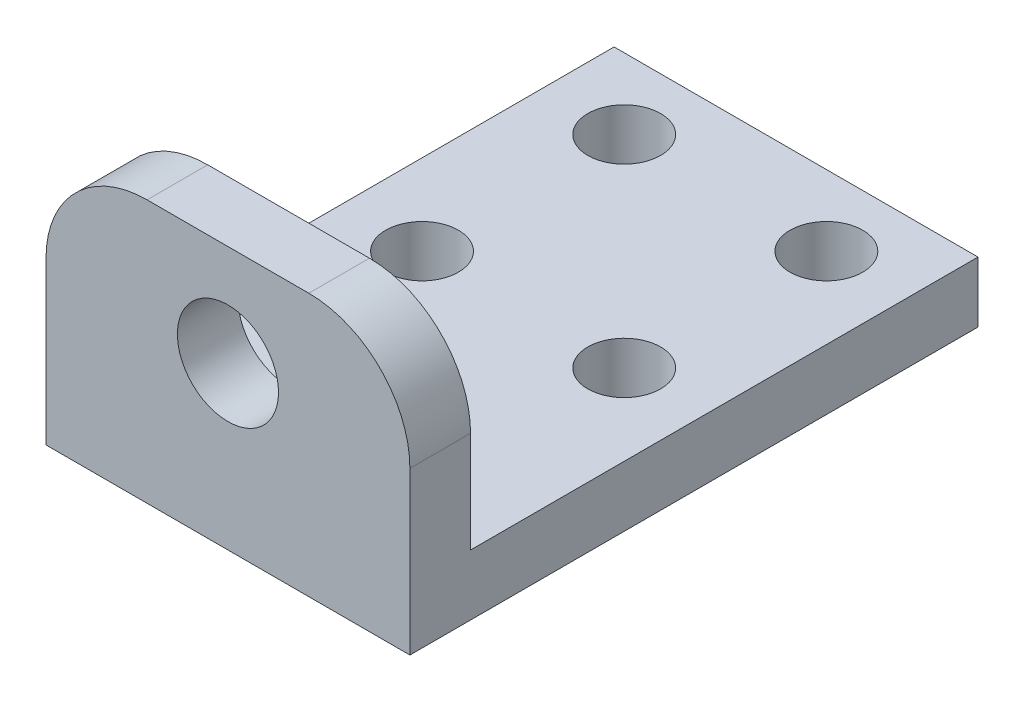
SolidWorks part; units mm, degrees
ref_plane "Front Plane" through (0, 0, 0) normal (0, 0, 1) x (1, 0, 0)
ref_plane "Top Plane" through (0, 0, 0) normal (0, 1, 0) x (1, 0, 0)
ref_plane "Right Plane" through (0, 0, 0) normal (1, 0, 0) x (0, 0, -1)
sketch "Sketch1" plane through (0, 0, 0) normal (1, 0, 0) x (0, 0, -1)
  line L0 (0, 0) -> (28.1, 0)
  line L1 (28.1, 0) -> (28.1, 3)
  line L2 (28.1, 3) -> (3, 3)
  line L3 (3, 3) -> (3, 13)
  line L4 (3, 13) -> (0, 13)
  line L5 (0, 13) -> (0, 0)
  dimension "D1" = 3
  dimension "D2" = 13
  dimension "D3" = 28.1
extrude "Boss-Extrude1" add sketch "Sketch1" along normal blind 18
sketch "Sketch2" plane through (0, 0, 0) normal (0, 0, 1) x (1, 0, 0)
  line L0 (0, 0) -> (18, 0) construction
  line L2 (9, 0) -> (9, 8) construction
  line L3 (18, 13) -> (0, 13) construction
  point P7 (9, 8)
  point P13 (9, 8)
  dimension "D1" = 5
hole_wizard "Ø5.0mm Dowel Hole1" positions "Sketch2" profile "Sketch3" hole size "Ø5.0" standard "ANSI Metric"
sketch "Sketch3" plane through (9, 8, 0) normal (1, 0, 0) x (0, -1, 0)
  line L0 (0, 0) -> (0, 4.5022)
  line L1 (0, 4.5022) -> (2.5, 3)
  line L2 (2.5, 3) -> (2.5, 0)
  line L5 (2.5, 0) -> (0, 0)
  line L10 (0, 4.5022) -> (-2.5, 3) construction
  line L11 (0, -6.35) -> (0, 107.95) construction
  dimension "Hole Dia." = 5
  dimension "Hole Depth" = 3
  dimension "Drill Angle" = 118
fillet "Fillet1" radius 5 2 edges at (0, 13, -1.5) (18, 13, -1.5)
sketch "Sketch4" plane through (0, 3, 0) normal (0, 1, 0) x (1, 0, 0)
  line L0 (9, 28.1) -> (9, 3) construction
  line L1 (18, 28.1) -> (0, 28.1) construction
  line L2 (18, 3) -> (0, 3) construction
  line L4 (18, 19.6) -> (0, 19.6) construction
  line L7 (0, 28.1) -> (0, 3) construction
  line L8 (18, 28.1) -> (18, 3) construction
  point P42 (4, 24.6)
  point P45 (4, 14.6)
  point P46 (14, 14.6)
  point P47 (14, 24.6)
  dimension "D1" = 5
  dimension "D2" = 5
  dimension "D3" = 8.5
hole_wizard "M3 Clearance Hole1" positions "Sketch4" profile "Sketch5" hole size "M3" standard "ANSI Metric" end condition through all
sketch "Sketch5" plane through (14, 3, -24.6) normal (1, 0, 0) x (0, 0, 1)
  line L0 (0, 0) -> (0, 3)
  line L1 (0, 3) -> (1.8, 3)
  line L2 (1.8, 3) -> (1.8, 0)
  line L5 (1.8, 0) -> (0, 0)
  line L11 (0, -6.35) -> (0, 107.95) construction
  dimension "Thru Hole Dia." = 3.6
  dimension "Thru Hole Depth" = 3
equation "\"Length\"= 31.1 - 3"
equation "\"D3@Sketch1\"=\"Length\""
